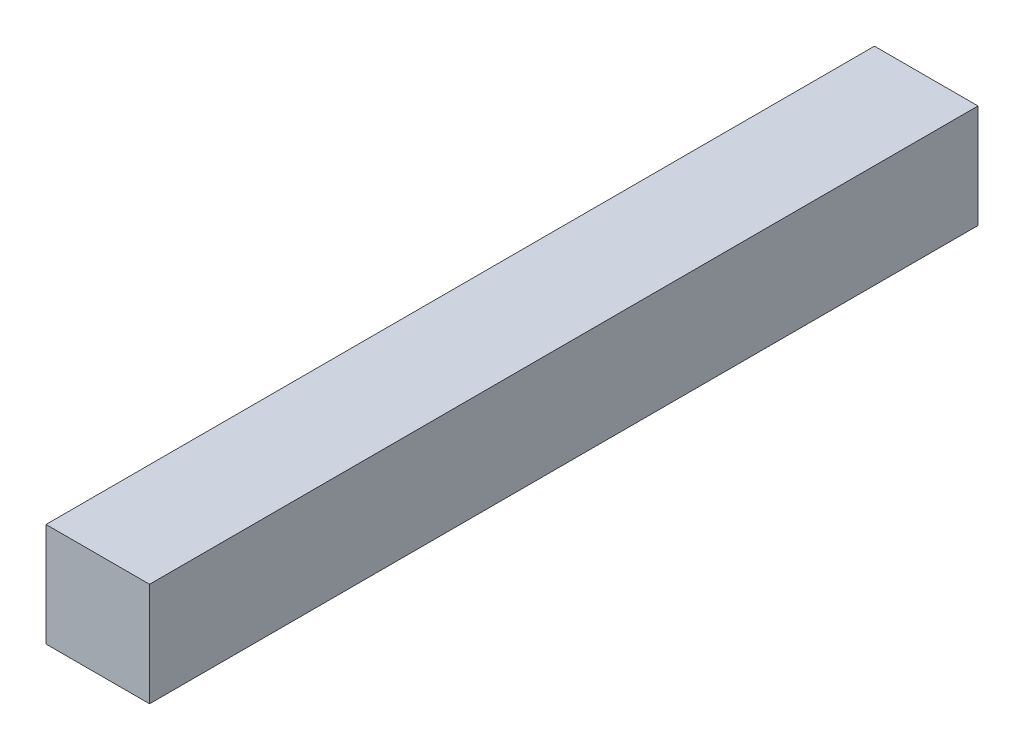
SolidWorks part; units mm, degrees
ref_plane "Front Plane" through (0, 0, 0) normal (0, 0, 1) x (1, 0, 0)
ref_plane "Top Plane" through (0, 0, 0) normal (0, 1, 0) x (1, 0, 0)
ref_plane "Right Plane" through (0, 0, 0) normal (1, 0, 0) x (0, 0, -1)
sketch "Sketch1" plane through (0, 0, 0) normal (1, 0, 0) x (0, 0, -1)
  line L1 (-40000, 0) -> (40000, 0)
  line L2 (-40000, 0) -> (-40000, 10000)
  line L3 (-40000, 10000) -> (40000, 10000)
  line L4 (40000, 0) -> (40000, 10000)
extrude "Boss-Extrude1" add sketch "Sketch1" along normal blind 10000
